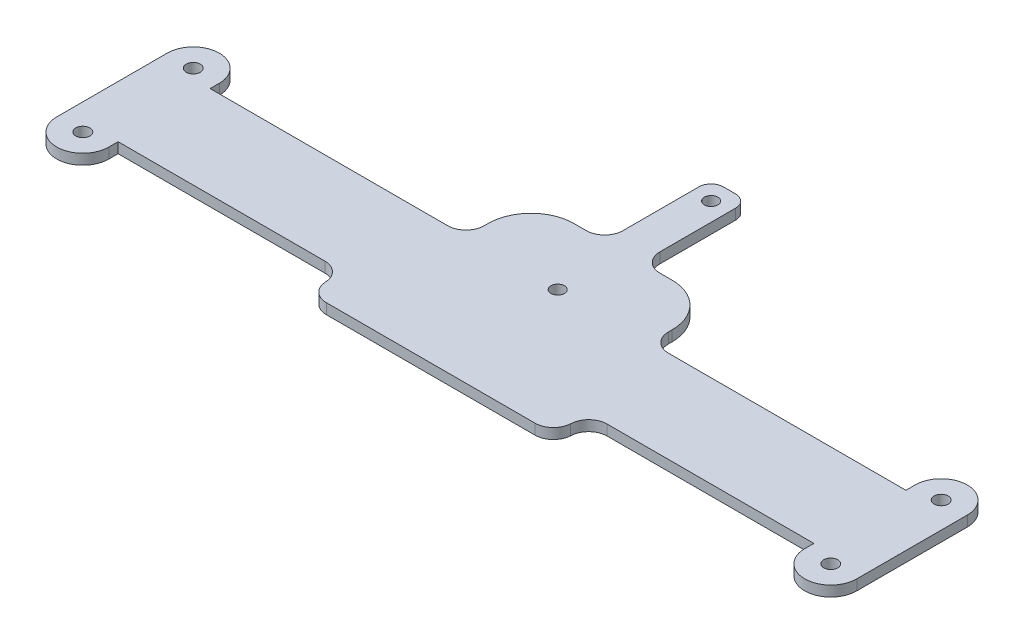
SolidWorks part; units mm, degrees
ref_plane "Płaszczyzna przednia" through (0, 0, 0) normal (0, 0, 1) x (1, 0, 0)
ref_plane "Płaszczyzna górna" through (0, 0, 0) normal (0, 1, 0) x (1, 0, 0)
ref_plane "Płaszczyzna prawa" through (0, 0, 0) normal (1, 0, 0) x (0, 0, -1)
sketch "Szkic1" plane through (0, 7.0875, 0) normal (0, -1, 0) x (1, 0, 0)
  line L0 (-166.869, 45.27) -> (-166.869, 48.27) construction
  line L1 (-166.869, 45.27) -> (-166.869, 48.27)
  line L2 (-44.969, 30.27) -> (-44.969, 31.77) construction
  line L3 (-36.469, 33.27) -> (-36.469, 30.27) construction
  line L4 (-36.469, 48.27) -> (-36.469, 45.27) construction
  line L5 (-44.969, 46.77) -> (-44.969, 48.27) construction
  line L6 (-158.369, 31.77) -> (-158.369, 30.27) construction
  line L7 (-166.869, 30.27) -> (-166.869, 33.27) construction
  line L8 (-158.369, 48.27) -> (-158.369, 46.77) construction
  line L9 (-44.969, 30.27) -> (-44.969, 31.77)
  line L10 (-36.469, 33.27) -> (-36.469, 30.27)
  line L11 (-36.469, 48.27) -> (-36.469, 45.27)
  line L12 (-44.969, 46.77) -> (-44.969, 48.27)
  line L13 (-158.369, 31.77) -> (-158.369, 30.27)
  line L14 (-166.869, 30.27) -> (-166.869, 33.27)
  line L15 (-158.369, 48.27) -> (-158.369, 46.77)
  line L16 (-166.869, 33.27) -> (-166.869, 45.27)
  line L17 (-36.469, 45.27) -> (-36.469, 33.27)
  line L18 (-158.369, 46.77) -> (-124.669, 46.77)
  line L19 (-44.969, 31.77) -> (-83.669, 31.77)
  line L20 (-101.669, 68.1389) -> (-101.669, -15.6805) construction
  line L21 (-116.669, 28.77) -> (-116.669, 28.17)
  line L22 (-109.669, 21.17) -> (-107.669, 21.17)
  line L23 (-86.669, 28.17) -> (-86.669, 28.77)
  line L24 (-119.669, 31.77) -> (-158.369, 31.77)
  line L26 (-104.669, 18.17) -> (-104.669, 5.82)
  line L28 (-102.669, 3.82) -> (-100.669, 3.82)
  line L29 (-98.669, 5.82) -> (-98.669, 18.17)
  line L30 (-95.669, 21.17) -> (-93.669, 21.17)
  line L49 (-121.669, 49.77) -> (-121.669, 49.52)
  line L50 (-118.669, 52.52) -> (-84.669, 52.52)
  line L51 (-81.669, 49.52) -> (-81.669, 49.77)
  line L52 (-78.669, 46.77) -> (-44.969, 46.77)
  arc A0 (-44.969, 30.27) -> (-36.469, 30.27) centre (-40.719, 30.27) ccw construction
  arc A1 (-36.469, 48.27) -> (-44.969, 48.27) centre (-40.719, 48.27) ccw construction
  arc A2 (-166.869, 30.27) -> (-158.369, 30.27) centre (-162.619, 30.27) ccw construction
  arc A3 (-158.369, 48.27) -> (-166.869, 48.27) centre (-162.619, 48.27) ccw construction
  arc A4 (-44.969, 30.27) -> (-36.469, 30.27) centre (-40.719, 30.27) ccw
  arc A5 (-36.469, 48.27) -> (-44.969, 48.27) centre (-40.719, 48.27) ccw
  arc A6 (-166.869, 30.27) -> (-158.369, 30.27) centre (-162.619, 30.27) ccw
  arc A7 (-158.369, 48.27) -> (-166.869, 48.27) centre (-162.619, 48.27) ccw
  arc A8 (-86.669, 28.17) -> (-93.669, 21.17) centre (-93.669, 28.17) cw
  arc A9 (-116.669, 28.17) -> (-109.669, 21.17) centre (-109.669, 28.17) ccw
  arc A10 (-83.669, 31.77) -> (-86.669, 28.77) centre (-83.669, 28.77) ccw
  arc A11 (-119.669, 31.77) -> (-116.669, 28.77) centre (-119.669, 28.77) cw
  arc A16 (-163.769, 30.27) -> (-161.469, 30.27) centre (-162.619, 30.27) ccw construction
  arc A17 (-161.469, 48.27) -> (-163.769, 48.27) centre (-162.619, 48.27) ccw construction
  arc A18 (-39.569, 48.27) -> (-41.869, 48.27) centre (-40.719, 48.27) ccw construction
  arc A19 (-41.869, 30.27) -> (-39.569, 30.27) centre (-40.719, 30.27) ccw construction
  circle A24 centre (-162.619, 30.27) radius 1.15
  circle A25 centre (-162.619, 48.27) radius 1.15
  circle A26 centre (-40.719, 48.27) radius 1.15
  circle A27 centre (-40.719, 30.27) radius 1.15
  arc A28 (-81.669, 49.77) -> (-78.669, 46.77) centre (-78.669, 49.77) ccw
  arc A29 (-84.669, 52.52) -> (-81.669, 49.52) centre (-84.669, 49.52) cw
  arc A30 (-121.669, 49.52) -> (-118.669, 52.52) centre (-118.669, 49.52) cw
  arc A31 (-121.669, 49.77) -> (-124.669, 46.77) centre (-124.669, 49.77) cw
  circle A32 centre (-101.669, 31.82) radius 1.1
  circle A33 centre (-101.669, 6.82) radius 1.1
  arc A34 (-104.669, 5.82) -> (-102.669, 3.82) centre (-102.669, 5.82) ccw
  arc A35 (-100.669, 3.82) -> (-98.669, 5.82) centre (-100.669, 5.82) ccw
  arc A36 (-98.669, 18.17) -> (-95.669, 21.17) centre (-95.669, 18.17) cw
  arc A37 (-104.669, 18.17) -> (-107.669, 21.17) centre (-107.669, 18.17) ccw
  point P35 (-116.669, 31.77)
  point P50 (-81.669, 46.77)
  point P60 (-162.619, 52.52)
  point P79 (-98.669, 21.17)
  dimension "D4" = 7
  dimension "D5" = 3
  dimension "D6" = 31.35
  dimension "D7" = 20
  dimension "D9" = 3
  dimension "D12" = 2.2
  dimension "D16" = 2.2
  dimension "D17" = 2
  dimension "D19" = 3
  dimension "D1" = 15
  dimension "D2" = 15
  dimension "D3" = 25.6
  dimension "D8" = 20
  dimension "D10" = 0
  dimension "D11" = 20.7
  dimension "D13" = 25
  dimension "D14" = 3
  dimension "D15" = 3
  dimension "D18" = 3
extrude "Dodanie-wyciągnięcie1" add sketch "Szkic1" along normal blind 1.7
